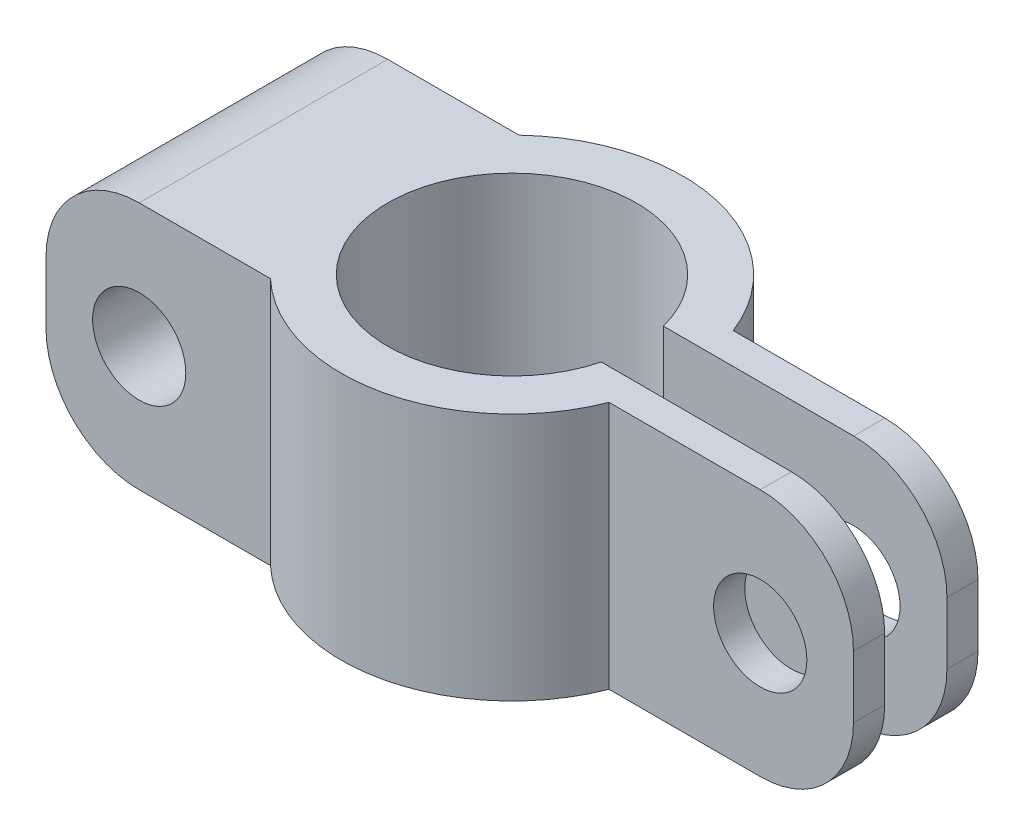
SolidWorks part; units mm, degrees
material "1060 合金"
ref_plane "前视基准面" through (0, 0, 0) normal (0, 0, 1) x (1, 0, 0)
ref_plane "上视基准面" through (0, 0, 0) normal (0, 1, 0) x (1, 0, 0)
ref_plane "右视基准面" through (0, 0, 0) normal (1, 0, 0) x (0, 0, -1)
other "Configuration Table"
sketch "草图1" plane through (0, 0, 0) normal (0, 1, 0) x (1, 0, 0)
  line L0 (-20.5141, 0) -> (20.4734, 0) construction
  line L1 (8.9351, 1) -> (13, 1)
  line L2 (5.4083, -1) -> (12.9955, -1)
  line L3 (5.1235, 2) -> (13, 2)
  line L4 (5.1235, -2) -> (12.9908, -2)
  line L5 (13, 2) -> (13, 1)
  line L6 (12.9955, -1) -> (12.9908, -2)
  line L7 (-3.7749, 4) -> (-11, 4)
  line L8 (8.9351, 1) -> (3.873, 1)
  line L9 (5.4083, -1) -> (3.873, -1)
  line L10 (-11, 4) -> (-11, -4)
  line L11 (-11, -4) -> (-3.7749, -4)
  arc A0 (3.873, 1) -> (3.873, -1) centre (0, 0) ccw
  arc A1 (5.1235, 2) -> (-3.7749, 4) centre (0, 0) ccw
  arc A2 (-3.7749, -4) -> (5.1235, -2) centre (0, 0) ccw
  dimension "D1" = 1
  dimension "D10" = 4
  dimension "D11" = 5.5
  dimension "D2" = 1
  dimension "D3" = 1
  dimension "D4" = 1
  dimension "D5" = 4
  dimension "D6" = 4
  dimension "D7" = 11
  dimension "D8" = 13
  dimension "D9" = 13
extrude "凸台-拉伸1" add sketch "草图1" along normal blind 8
fillet "圆角2" radius 3 1 edges at (-11, 8, 0)
fillet "圆角3" radius 3 1 edges at (-11, 0, 0)
fillet "圆角4" radius 3 1 edges at (12.9931, 8, 1.5)
fillet "圆角5" radius 3 1 edges at (12.9931, 0, 1.5)
fillet "圆角6" radius 3 1 edges at (13, 8, -1.5)
fillet "圆角7" radius 3 1 edges at (13, 0, -1.5)
sketch "草图3" plane through (0, 0, 4) normal (0, 0, 1) x (1, 0, 0)
  line L0 (-8, 0) -> (-3.7749, 0) construction
  line L1 (-11, 5) -> (-11, 3) construction
  circle A0 centre (-8, 4) radius 1.5
  point P0 (-8, 4)
  dimension "D1" = 4
  dimension "D2" = 3
extrude "切除-拉伸1" cut sketch "草图3" against normal blind 20
sketch "草图4" plane through (0, 0, 2) normal (0, 0, 1) x (1, 0, 0)
  line L0 (5.1235, 0) -> (9.9908, 0) construction
  line L1 (12.9908, 5) -> (12.9908, 3) construction
  circle A0 centre (9.9908, 4) radius 1.5
  point P0 (9.9908, 4)
  dimension "D1" = 4
  dimension "D2" = 3
extrude "切除-拉伸2" cut sketch "草图4" against normal blind 20
